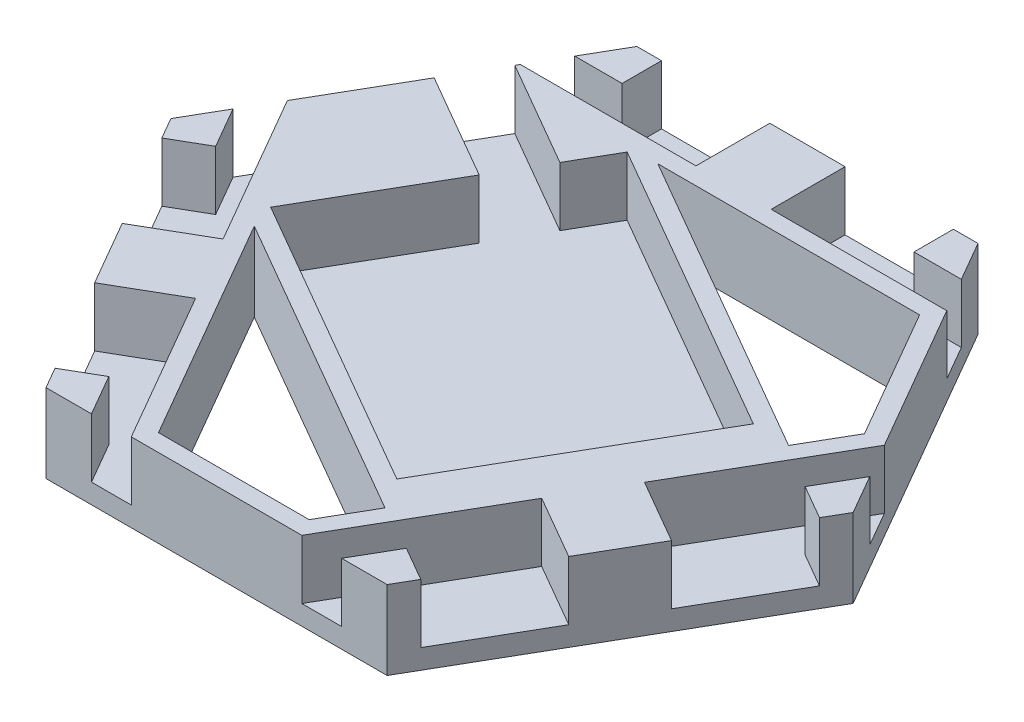
SolidWorks part; units mm, degrees
ref_plane "Front Plane" through (0, 0, 0) normal (0, 0, 1) x (1, 0, 0)
ref_plane "Top Plane" through (0, 0, 0) normal (0, 1, 0) x (1, 0, 0)
ref_plane "Right Plane" through (0, 0, 0) normal (1, 0, 0) x (0, 0, -1)
sketch "Sketch1" plane through (0, 0, 0) normal (0, 1, 0) x (1, 0, 0)
  line L0 (0, 0) -> (39.7226, 0) construction
  line L1 (0, 0) -> (0, 31.3322) construction
  line L3 (69.282, 0) -> (34.641, 60)
  line L4 (34.641, 60) -> (-34.641, 60)
  line L5 (-34.641, 60) -> (-69.282, 0)
  line L6 (-69.282, 0) -> (-34.641, -60)
  line L7 (-34.641, -60) -> (34.641, -60)
  line L8 (34.641, -60) -> (69.282, 0)
  circle A1 centre (0, 0) radius 60 construction
  dimension "D1" = 120
extrude "Boss-Extrude1" add sketch "Sketch1" along normal blind 16
sketch "Sketch2" plane through (0, 16, 0) normal (0, 1, 0) x (1, 0, 0)
  line L0 (-29.641, 60) -> (-29.641, 45)
  line L1 (34.641, 60) -> (-34.641, 60) construction
  line L2 (-29.641, 45) -> (-7.641, 45)
  line L3 (-7.641, 45) -> (-7.641, 60)
  line L4 (7.641, 60) -> (7.641, 45)
  line L5 (7.641, 45) -> (29.641, 45)
  line L6 (29.641, 45) -> (29.641, 60)
  line L7 (66.782, -4.3301) -> (53.7917, 3.1699)
  line L8 (53.7917, 3.1699) -> (42.7917, -15.8827)
  line L9 (42.7917, -15.8827) -> (55.782, -23.3827)
  line L10 (48.141, -36.6173) -> (35.1506, -29.1173)
  line L11 (35.1506, -29.1173) -> (24.1506, -48.1699)
  line L12 (24.1506, -48.1699) -> (37.141, -55.6699)
  line L13 (-37.141, -55.6699) -> (-24.1506, -48.1699)
  line L14 (-24.1506, -48.1699) -> (-35.1506, -29.1173)
  line L15 (-35.1506, -29.1173) -> (-48.141, -36.6173)
  line L16 (-55.782, -23.3827) -> (-42.7917, -15.8827)
  line L17 (-42.7917, -15.8827) -> (-53.7917, 3.1699)
  line L18 (-53.7917, 3.1699) -> (-66.782, -4.3301)
  line L19 (-29.641, 60) -> (-7.641, 60)
  line L20 (7.641, 60) -> (29.641, 60)
  line L21 (66.782, -4.3301) -> (55.782, -23.3827)
  line L22 (48.141, -36.6173) -> (37.141, -55.6699)
  line L23 (-48.141, -36.6173) -> (-37.141, -55.6699)
  line L24 (-66.782, -4.3301) -> (-55.782, -23.3827)
  point P10 (-7.641, 52.5)
  point P11 (29.641, 52.5)
  dimension "D1" = 5
  dimension "D2" = 5
  dimension "D3" = 22
  dimension "D4" = 22
  dimension "D5" = 15
  dimension "D6" = 15
  dimension "D7" = 3
extrude "Cut-Extrude1" cut sketch "Sketch2" against normal blind 12
sketch "Sketch3" plane through (0, 16, 0) normal (0, 1, 0) x (1, 0, 0)
  line L0 (0, 0) -> (-51.9615, 30) construction
  line L1 (-43.5609, -5.4497) -> (17.0609, -40.4497)
  line L2 (-0.0025, 0.0015) -> (34.6385, 60.0015)
  line L3 (-43.5609, -5.4497) -> (-17.0609, 40.4497)
  line L4 (17.0609, -40.4497) -> (43.5609, 5.4497)
  line L5 (-17.0609, 40.4497) -> (43.5609, 5.4497)
  line L6 (-43.5609, -5.4497) -> (43.5609, 5.4497) construction
  line L7 (17.0609, -40.4497) -> (-17.0609, 40.4497) construction
  line L8 (-22.0609, 31.7894) -> (-28.0609, 21.3971)
  line L9 (-22.0609, 31.7894) -> (-43.7115, 44.2894)
  line L10 (-28.0609, 21.3971) -> (-49.7115, 33.8971)
  line L11 (-43.7115, 44.2894) -> (-49.7115, 33.8971)
  line L12 (-34.641, 60) -> (-69.282, 0) construction
  point P4 (0, 0)
  line M19 (-34.641, 60) -> (-69.282, 0)
  dimension "D1" = 70
  dimension "D2" = 53
  dimension "D3" = 10
  dimension "D4" = 12
extrude "Cut-Extrude2" cut sketch "Sketch3" against normal up to vertex (12 mm away) and the other way through all contours L5 L3 L1 L2 | L5 L2 L1 L4 | L10 L3 L9 M19
sketch "Sketch4" plane through (0, 16, 0) normal (0, 1, 0) x (1, 0, 0)
  line L0 (-53.7917, 3.1699) -> (-59.8538, -0.3301)
  line L1 (-53.7917, 3.1699) -> (-66.782, -4.3301) construction
  line L2 (-59.8538, -0.3301) -> (-64.6632, 8)
  line L3 (-49.7115, 33.8971) -> (-69.282, 0) construction
  line L4 (-64.6632, 8) -> (-60.6218, 15)
  line L5 (-60.6218, 15) -> (-53.7917, 3.1699)
  line L6 (-24.1506, -48.1699) -> (-30.2128, -51.6699)
  line L7 (-37.141, -55.6699) -> (-24.1506, -48.1699) construction
  line L8 (-30.2128, -51.6699) -> (-25.4034, -60)
  line L9 (-34.641, -60) -> (34.641, -60) construction
  line L10 (-25.4034, -60) -> (-17.3205, -60)
  line L11 (-17.3205, -60) -> (-24.1506, -48.1699)
  line L12 (43.3013, 45) -> (29.641, 45)
  line L13 (29.641, 45) -> (29.641, 52)
  line L14 (29.641, 52) -> (39.2598, 52)
  line L15 (39.2598, 52) -> (43.3013, 45)
  line L16 (-43.3013, 45) -> (-29.641, 45)
  line L17 (-29.641, 45) -> (-29.641, 52)
  line L18 (-29.641, 52) -> (-39.2598, 52)
  line L19 (-39.2598, 52) -> (-43.3013, 45)
  line L20 (17.3205, -60) -> (24.1506, -48.1699)
  line L21 (24.1506, -48.1699) -> (30.2128, -51.6699)
  line L22 (30.2128, -51.6699) -> (25.4034, -60)
  line L23 (25.4034, -60) -> (17.3205, -60)
  line L24 (60.6218, 15) -> (53.7917, 3.1699)
  line L25 (53.7917, 3.1699) -> (59.8538, -0.3301)
  line L26 (59.8538, -0.3301) -> (64.6632, 8)
  line L27 (64.6632, 8) -> (60.6218, 15)
  point P36 (0, 0)
  dimension "D1" = 7
  dimension "D2" = 3
extrude "Cut-Extrude4" cut sketch "Sketch4" against normal up to vertex (12 mm away)
sketch "Sketch7" plane through (0, 16, 0) normal (0, 1, 0) x (1, 0, 0)
  line L0 (-41.8801, -10.4615) -> (-15.2998, -56.5)
  line L1 (-15.2998, -56.5) -> (15.2998, -56.5)
  line L2 (15.2998, -56.5) -> (20.9401, -46.7308)
  line L3 (20.9401, -46.7308) -> (-41.8801, -10.4615)
  line L4 (-17.3205, -60) -> (-35.1506, -29.1173) construction
  line L5 (-43.5609, -5.4497) -> (17.0609, -40.4497) construction
  line L6 (35.1506, -29.1173) -> (17.3205, -60) construction
  line L7 (-17.3205, -60) -> (17.3205, -60) construction
  line L8 (-17.3205, -60) -> (-35.1506, -29.1173) construction
  line L9 (35.1506, -29.1173) -> (17.3205, -60) construction
  line L10 (-11.8801, 41.5) -> (50.9401, 5.2308)
  line L11 (50.9401, 5.2308) -> (56.5803, 15)
  line L12 (56.5803, 15) -> (41.2805, 41.5)
  line L13 (41.2805, 41.5) -> (-11.8801, 41.5)
  line L14 (7.641, 45) -> (43.3013, 45) construction
  line L15 (60.6218, 15) -> (43.3013, 45) construction
  line L16 (60.6218, 15) -> (42.7917, -15.8827) construction
  line L17 (-17.0609, 40.4497) -> (43.5609, 5.4497) construction
  line L18 (-17.0609, 40.4497) -> (43.5609, 5.4497) construction
  dimension "D1" = 3.5
  dimension "D2" = 3.5
  dimension "D3" = 3.5
  dimension "D4" = 3.5
  dimension "D5" = 3.5
  dimension "D6" = 3.5
  dimension "D7" = 3.5
  dimension "D8" = 3.5
extrude "Cut-Extrude5" cut sketch "Sketch7" against normal through all
equation "\"D2@Sketch2\"=\"D1@Sketch2\""
equation "\"D4@Sketch2\"=\"D3@Sketch2\""
equation "\"D6@Sketch2\"=\"D5@Sketch2\""
